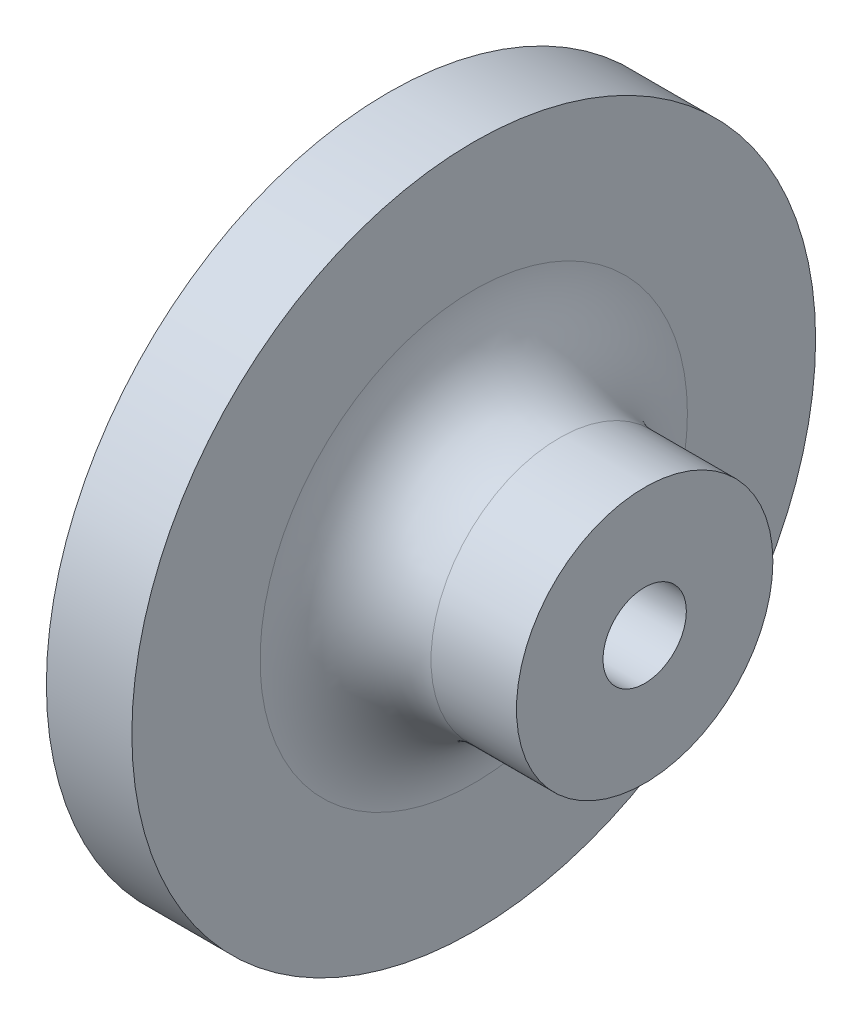
SolidWorks part; units mm, degrees
ref_plane "Plan de face" through (0, 0, 0) normal (1, 0, 0) x (0, 1, 0)
ref_plane "Plan de dessus" through (0, 0, 0) normal (0, 0, 1) x (0, 1, 0)
ref_plane "Plan de droite" through (0, 0, 0) normal (0, 1, 0) x (-1, 0, 0)
sketch "Esquisse1" plane through (0, 0, 0) normal (1, 0, 0) x (0, 1, 0)
  circle A0 centre (0, 0) radius 40
  circle A1 centre (0, 32) radius 5.5
  circle A2 centre (12.2459, 29.5641) radius 5.5
  circle A3 centre (22.6274, 22.6274) radius 5.5
  circle A4 centre (29.5641, 12.2459) radius 5.5
  circle A5 centre (32, 0) radius 5.5
  circle A6 centre (29.5641, -12.2459) radius 5.5
  circle A7 centre (22.6274, -22.6274) radius 5.5
  circle A8 centre (12.2459, -29.5641) radius 5.5
  circle A9 centre (0, -32) radius 5.5
  circle A10 centre (-12.2459, -29.5641) radius 5.5
  circle A11 centre (-22.6274, -22.6274) radius 5.5
  circle A12 centre (-29.5641, -12.2459) radius 5.5
  circle A13 centre (-32, 0) radius 5.5
  circle A14 centre (-29.5641, 12.2459) radius 5.5
  circle A15 centre (-22.6274, 22.6274) radius 5.5
  circle A16 centre (-12.2459, 29.5641) radius 5.5
  circle A17 centre (-11.4293, 17.1051) radius 5.5
  circle A18 centre (4.0134, 20.1768) radius 5.5
  circle A19 centre (17.1051, 11.4293) radius 5.5
  circle A20 centre (20.1768, -4.0134) radius 5.5
  circle A21 centre (11.4293, -17.1051) radius 5.5
  circle A22 centre (-4.0134, -20.1768) radius 5.5
  circle A23 centre (-17.1051, -11.4293) radius 5.5
  circle A24 centre (-20.1768, 4.0134) radius 5.5
  circle A25 centre (5.5277, 8.2728) radius 5.5
  circle A26 centre (8.2728, -5.5277) radius 5.5
  circle A27 centre (-5.5277, -8.2728) radius 5.5
  circle A28 centre (-8.2728, 5.5277) radius 5.5
  point P37 (0, 0)
  point P54 (0, 0)
  point P64 (0, 0)
  dimension "D1" = 80
  dimension "D2" = 11
  dimension "D5" = 11
  dimension "D9" = 11
  dimension "D3" = 32
  dimension "D6" = 12.4858
  dimension "D7" = 12.4858
  dimension "D10" = 12
  dimension "D11" = 12
  dimension "D4" = 16
  dimension "D8" = 8
  dimension "D12" = 4
extrude "Boss.-Extru.1" add sketch "Esquisse1" along normal blind 10
sketch "Esquisse2" plane through (10, 0, 0) normal (1, 0, 0) x (0, 1, 0)
  circle A0 centre (0, 0) radius 40
extrude "Boss.-Extru.2" add sketch "Esquisse2" against normal blind 7
sketch "Esquisse3" plane through (10, 0, 0) normal (1, 0, 0) x (0, 1, 0)
  circle A0 centre (0, 0) radius 15
  dimension "D1" = 30
extrude "Boss.-Extru.3" add sketch "Esquisse3" along normal blind 20
fillet "Congé1" radius 10 1 edges at (10, 0, -15)
sketch "Esquisse4" plane through (30, 0, 0) normal (1, 0, 0) x (0, 1, 0)
  circle A0 centre (0, 0) radius 4.875
  dimension "D1" = 9.75
extrude "Enlèv. mat.-Extru.1" cut sketch "Esquisse4" against normal blind 16
